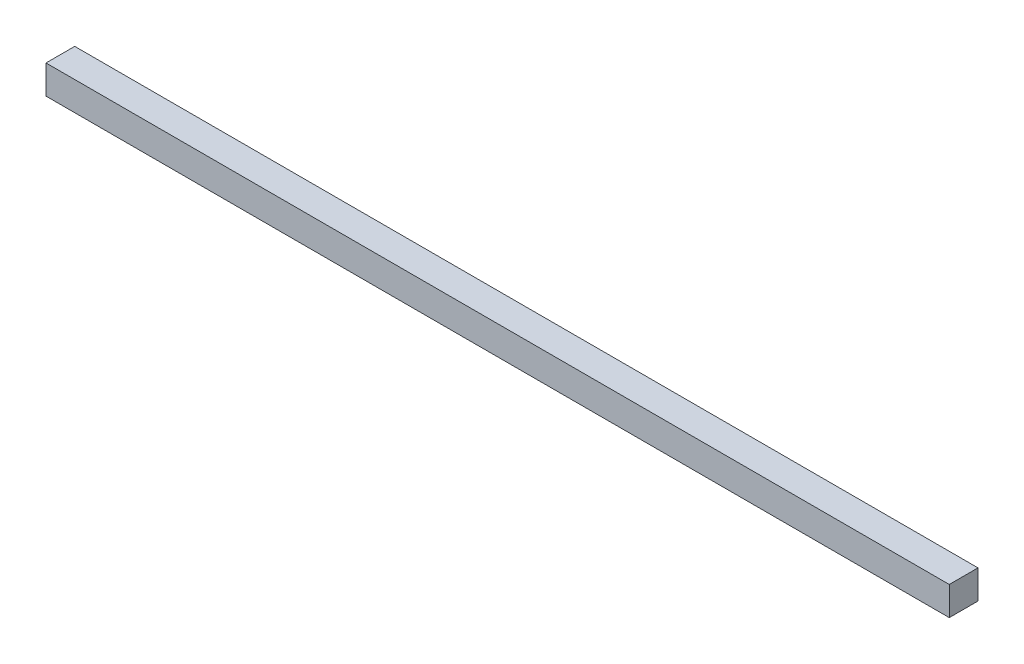
SolidWorks part; units mm, degrees
ref_plane "前视" through (0, 0, 0) normal (0, 0, 1) x (1, 0, 0)
ref_plane "上视" through (0, 0, 0) normal (0, 1, 0) x (1, 0, 0)
ref_plane "右视" through (0, 0, 0) normal (1, 0, 0) x (0, 0, -1)
sketch "草图1" plane through (0, 0, 0) normal (0, 0, 1) x (1, 0, 0)
  line L1 (0, 70) -> (2200, 70)
  line L2 (0, 70) -> (0, 0)
  line L3 (0, 0) -> (2200, 0)
  line L4 (2200, 70) -> (2200, 0)
  dimension "D1" = 2200
  dimension "D2" = 70
extrude "基体-拉伸" add sketch "草图1" along normal blind 70
